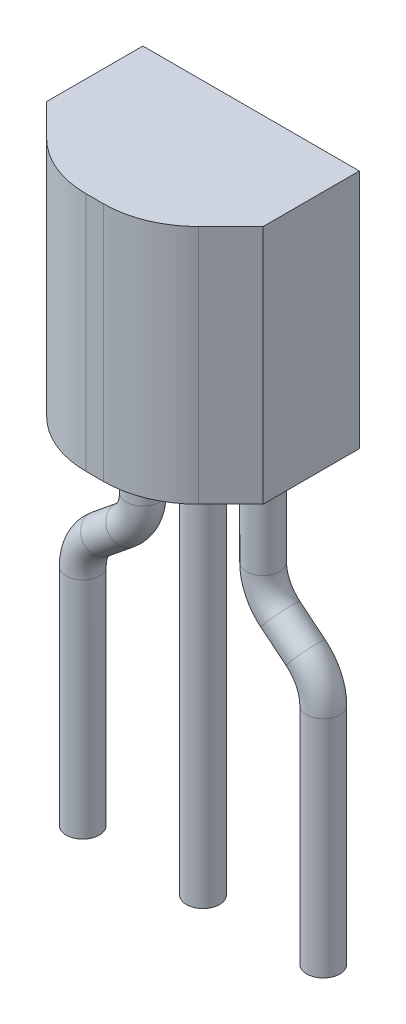
SolidWorks part; units mm, degrees
ref_plane "Front Plane" through (0, 0, 0) normal (0, 0, 1) x (1, 0, 0)
ref_plane "Top Plane" through (0, 0, 0) normal (0, 1, 0) x (1, 0, 0)
ref_plane "Right Plane" through (0, 0, 0) normal (1, 0, 0) x (0, 0, -1)
sketch "Sketch1" plane through (0, 0, 0) normal (0, 1, 0) x (1, 0, 0)
  line L0 (-1.016, -1.016) -> (0.254, -2.286)
  line L1 (-1.016, -1.016) -> (-1.016, 1.016)
  line L2 (-1.016, 1.016) -> (3.556, 1.016)
  line L3 (0.254, -2.286) -> (2.286, -2.286)
  line L4 (2.286, -2.286) -> (3.556, -1.016)
  line L5 (3.556, -1.016) -> (3.556, 1.016)
extrude "Boss-Extrude1" add sketch "Sketch1" along normal blind 5.08
sketch "Sketch2" plane through (0, 0, 0) normal (0, -1, 0) x (1, 0, 0)
  circle A0 centre (0, 0) radius 0.35
  circle A1 centre (1.27, 0) radius 0.35
  circle A2 centre (2.54, 0) radius 0.35
  dimension "D1" = 1.27
  dimension "D2" = 1.27
  dimension "D3" = 0.7
extrude "Boss-Extrude2" add sketch "Sketch2" along normal blind 2
ref_plane "Board Plane" through (0, -0.5, 0) normal (0, 1, 0) x (-1, 0, 0)
sketch "Component_Outline" plane through (0, -0.5, 0) normal (0, 1, 0) x (-1, 0, 0)
  line L0 (1.016, -1.016) -> (-3.556, -1.016)
  line L1 (-3.556, -1.016) -> (-3.556, 1.016)
  line L2 (-3.556, 1.016) -> (-2.286, 2.286)
  line L3 (-2.286, 2.286) -> (-0.254, 2.286)
  line L4 (-0.254, 2.286) -> (1.016, 1.016)
  line L5 (1.016, 1.016) -> (1.016, -1.016)
  point P4 (0, 0)
fillet "Fillet1" radius 2 2 edges at (2.286, 2.54, 2.286) (0.254, 2.54, 2.286)
sketch "Sketch3" plane through (0, -2, 0) normal (0, -1, 0) x (1, 0, 0)
  circle A0 centre (1.27, 0) radius 0.35
extrude "Boss-Extrude3" add sketch "Sketch3" along normal blind 6.8
sketch "Sketch4" plane through (0, -8.8, 0) normal (0, -1, 0) x (1, 0, 0)
  circle A0 centre (3.81, 0) radius 0.35
  dimension "D2" = 0.7
  dimension "D1" = 3.81
sketch "Sketch5" plane through (0, 0, 0) normal (0, 0, 1) x (1, 0, 0)
  line L0 (3.81, -8.8) -> (3.81, -4.0594)
  line L1 (3.46, -8.8) -> (4.16, -8.8) construction
  line L2 (3.4416, -3.284) -> (2.9084, -2.8498)
  line L3 (2.54, -2.0744) -> (2.54, -2)
  line L4 (2.19, -2) -> (2.89, -2) construction
  arc A0 (2.54, -2.0744) -> (2.9084, -2.8498) centre (3.54, -2.0744) ccw
  arc A1 (3.81, -4.0594) -> (3.4416, -3.284) centre (2.81, -4.0594) ccw
  dimension "D1" = 1
sweep "Sweep1" add profiles "Sketch4" path "Sketch5"
ref_plane "Plane1" through (1.27, 0, 0) normal (1, 0, 0) x (0, 0, -1)
mirror "Mirror1" about plane through (1.27, 0, 0) normal (1, 0, 0) of "Sweep1"
